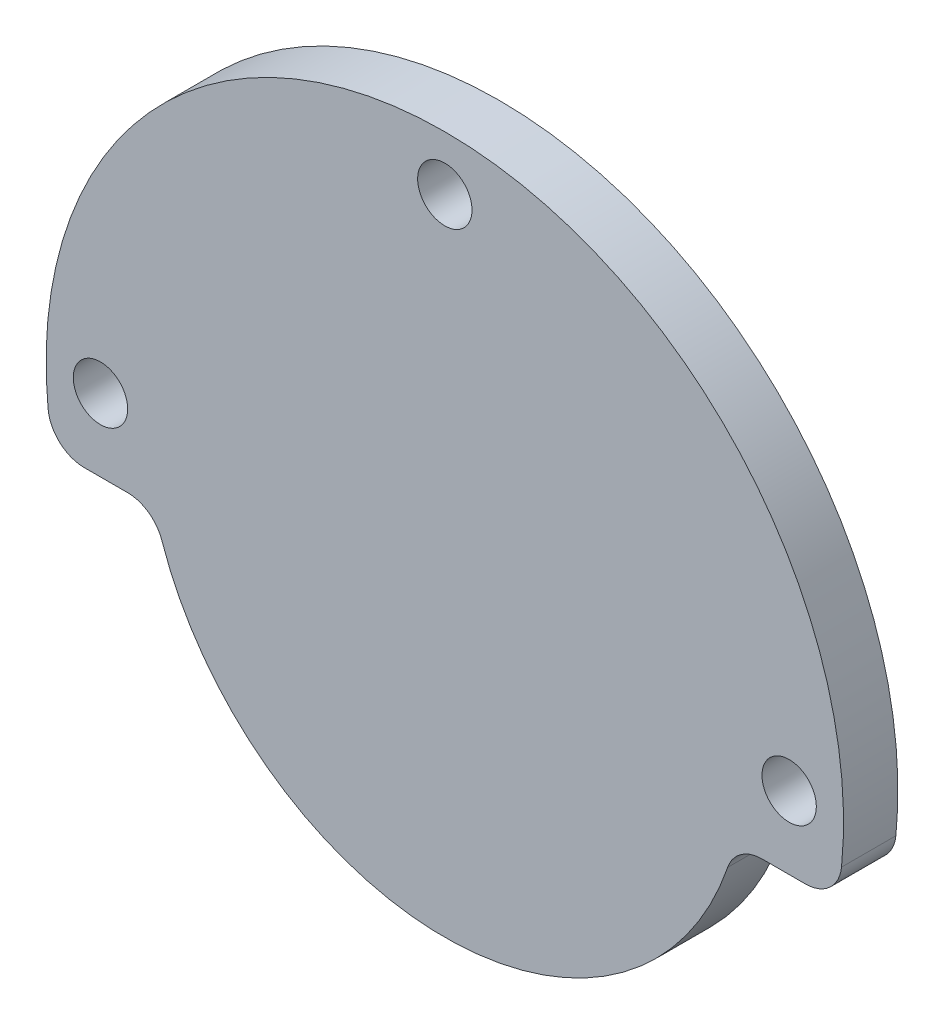
SolidWorks part; units mm, degrees
material "PC 高粘度"
ref_plane "前视基准面" through (0, 0, 0) normal (0, 0, 1) x (1, 0, 0)
ref_plane "上视基准面" through (0, 0, 0) normal (0, 1, 0) x (1, 0, 0)
ref_plane "右视基准面" through (0, 0, 0) normal (1, 0, 0) x (0, 0, -1)
sketch "草图1" plane through (0, 0, 0) normal (0, 0, 1) x (1, 0, 0)
  line L0 (-16.0078, -4) -> (-21.6333, -4)
  line L3 (0, -1.65) -> (0, 1.65) construction
  line L4 (16.0078, -4) -> (21.6333, -4)
  arc A2 (21.6333, -4) -> (-21.6333, -4) centre (0, 0) ccw
  arc A3 (19, 0) -> (-19, 0) centre (0, 0) ccw construction
  circle A4 centre (-19, 0) radius 1.5
  circle A5 centre (0, 19) radius 1.5
  circle A6 centre (19, 0) radius 1.5
  arc A7 (-16.0078, -4) -> (16.0078, -4) centre (0, 0) ccw
  dimension "D1" = 44
  dimension "D2" = 3
  dimension "D3" = 3
  dimension "D4" = 33
  dimension "D5" = 4
extrude "凸台-拉伸1" add sketch "草图1" along normal blind 3
fillet "圆角1" radius 2 4 edges at (21.6333, -4, 1.5) (16.0078, -4, 1.5) (-16.0078, -4, 1.5) (-21.6333, -4, 1.5)
